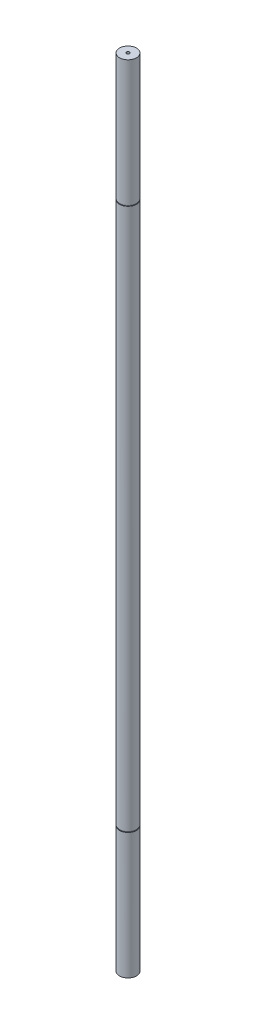
SolidWorks part; units mm, degrees
ref_plane "Front Plane" through (0, 0, 0) normal (0, 0, 1) x (1, 0, 0)
ref_plane "Top Plane" through (0, 0, 0) normal (0, 1, 0) x (1, 0, 0)
ref_plane "Right Plane" through (0, 0, 0) normal (1, 0, 0) x (0, 0, -1)
sketch "Sketch1" plane through (0, 0, 0) normal (0, 1, 0) x (1, 0, 0)
  circle A0 centre (0, 0) radius 6.35
  dimension "D1" = 12.7
extrude "Boss-Extrude1" add sketch "Sketch1" along normal blind 596.9
sketch "Sketch2" plane through (0, 596.9, 0) normal (0, 1, 0) x (1, 0, 0)
  circle A0 centre (0, 0) radius 1.1906
  dimension "D1" = 2.3813
extrude "Cut-Extrude1" cut sketch "Sketch2" against normal blind 609.6
ref_plane "Plane1" through (0, 95.25, 0) normal (0, -1, 0) x (-1, 0, 0)
sketch "Sketch6" plane through (0, 95.25, 0) normal (0, -1, 0) x (-1, 0, 0)
  circle A0 centre (0, 0) radius 5.9563
  dimension "D1" = 11.9126
extrude "Cut-Extrude2" cut sketch "Sketch6" along normal blind 0.635 flip side to cut
ref_plane "Plane2" through (0, 298.45, 0) normal (0, -1, 0) x (-1, 0, 0)
mirror "Mirror1" about plane through (0, 298.45, 0) normal (0, -1, 0) of "Cut-Extrude2"
